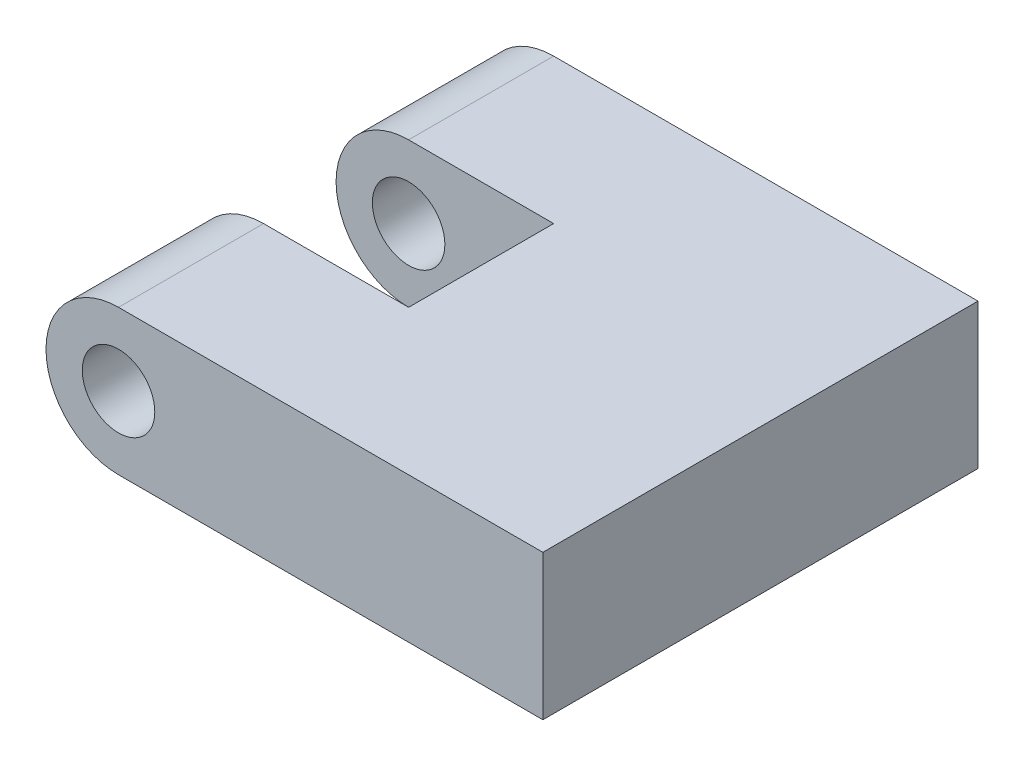
SolidWorks part; units mm, degrees
ref_plane "Front Plane" through (0, 0, 0) normal (0, 0, 1) x (1, 0, 0)
ref_plane "Top Plane" through (0, 0, 0) normal (0, 1, 0) x (1, 0, 0)
ref_plane "Right Plane" through (0, 0, 0) normal (1, 0, 0) x (0, 0, -1)
sketch "Sketch1" plane through (0, 0, 0) normal (0, 0, 1) x (1, 0, 0)
  line L0 (0, 10) -> (53.5123, 10)
  line L1 (53.5123, 10) -> (53.5123, -10)
  line L2 (53.5123, -10) -> (0, -10)
  circle A0 centre (0, 0) radius 10
  dimension "D1" = 20
extrude "Boss-Extrude1" add sketch "Sketch1" along normal blind 60 contours A0 | A0 L2 L1 L0
ref_plane "Plane1" through (0, 0, 0) normal (1, 0, 0) x (0, 0, -1)
sketch "Sketch2" plane through (0, 0, 0) normal (1, 0, 0) x (0, 0, -1)
  line L0 (0, 0) -> (-60, 0) construction
  line L1 (-60, 10) -> (-60, -10) construction
  line L3 (-20, 14.4724) -> (-40, 14.4724)
  line L4 (-20, 14.4724) -> (-20, -14.4724)
  line L5 (-20, -14.4724) -> (-40, -14.4724)
  line L6 (-40, 14.4724) -> (-40, -14.4724)
  line L7 (-20, 14.4724) -> (-40, -14.4724) construction
  line L8 (-20, -14.4724) -> (-40, 14.4724) construction
  point P5 (-30, 0)
  dimension "D1" = 20
extrude "Cut-Extrude1" cut sketch "Sketch2" against normal blind 40 and the other way blind 20
sketch "Sketch3" plane through (0, 0, 60) normal (0, 0, 1) x (1, 0, 0)
  circle A0 centre (0, 0) radius 5
  dimension "D1" = 10
extrude "Cut-Extrude3" cut sketch "Sketch3" against normal blind 120
ref_plane "Plane2" through (0, 0, 50) normal (0, 0, 1) x (1, 0, 0)
sketch "Sketch4" plane through (53.5123, 0, 0) normal (1, 0, 0) x (0, 0, -1)
  line L4 (0, -10) -> (0, 10)
  line L5 (0, 10) -> (-60, 10)
  line L6 (-60, 10) -> (-60, -10)
  line L7 (-60, -10) -> (0, -10)
  line L8 (0, -10) -> (0, 10)
  line L9 (0, 10) -> (-60, 10)
  line L10 (-60, 10) -> (-60, -10)
  line L11 (-60, -10) -> (0, -10)
  dimension "D1" = 0
extrude "Boss-Extrude2" add sketch "Sketch4" along normal blind 5
